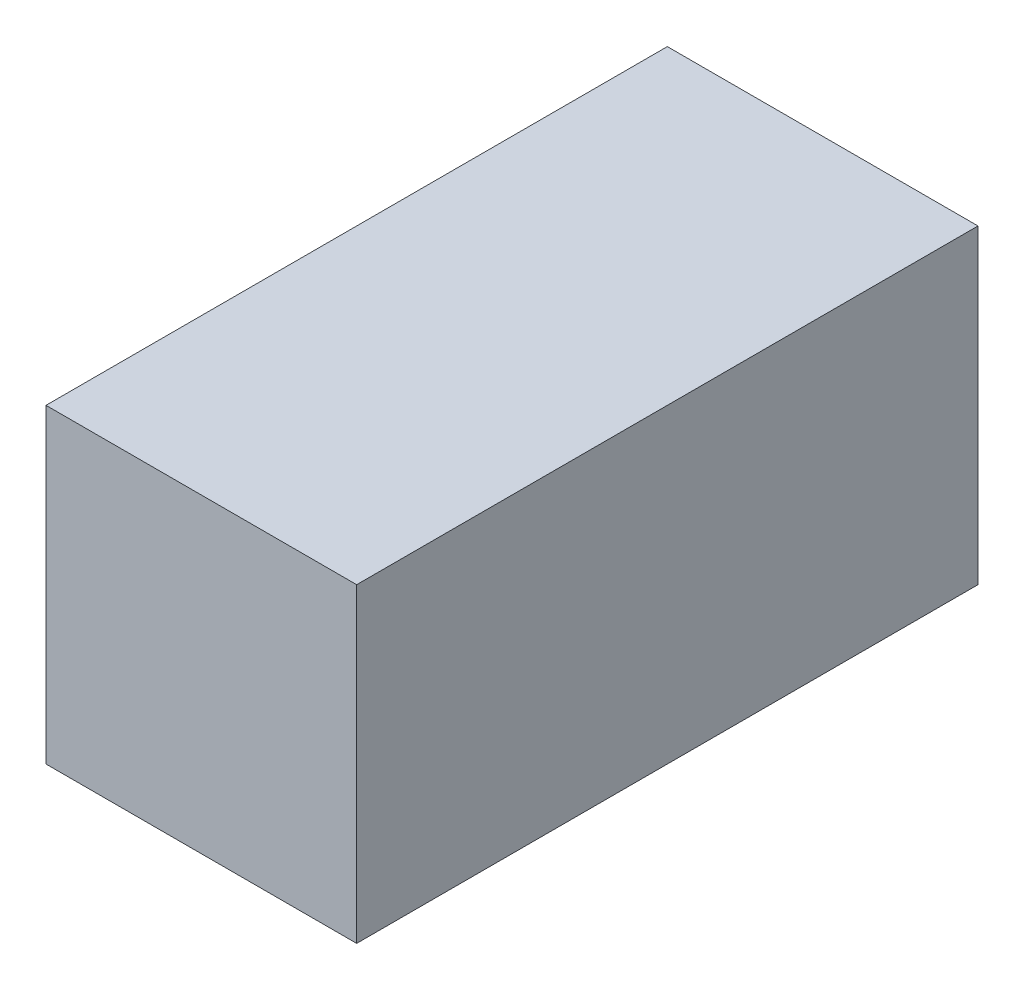
SolidWorks part; units mm, degrees
ref_plane "Front Plane" through (0, 0, 0) normal (0, 0, 1) x (1, 0, 0)
ref_plane "Top Plane" through (0, 0, 0) normal (0, 1, 0) x (1, 0, 0)
ref_plane "Right Plane" through (0, 0, 0) normal (1, 0, 0) x (0, 0, -1)
sketch "Sketch1" plane through (0, 0, 0) normal (0, 0, 1) x (1, 0, 0)
  line L1 (-9.4309, -12.2561) -> (10.5691, -12.2561)
  line L2 (-9.4309, -12.2561) -> (-9.4309, 7.7439)
  line L3 (-9.4309, 7.7439) -> (10.5691, 7.7439)
  line L4 (10.5691, -12.2561) -> (10.5691, 7.7439)
  line L5 (-9.4309, -12.2561) -> (10.5691, 7.7439) construction
  line L6 (-9.4309, 7.7439) -> (10.5691, -12.2561) construction
  dimension "D1" = 20
  dimension "D2" = 20
extrude "Boss-Extrude1" add sketch "Sketch1" along normal blind 40
sketch "Sketch2" plane through (0, 0, 0) normal (0, 0, -1) x (-1, 0, 0)
  line L0 (-0.5691, 7.7439) -> (-0.5691, -5.1168) construction
  line L1 (-10.5691, 7.7439) -> (9.4309, 7.7439) construction
  line L2 (-0.5691, -5.1168) -> (9.4309, -2.2561) construction
  line L3 (9.4309, 7.7439) -> (9.4309, -12.2561) construction
  line L4 (9.4309, -2.2561) -> (-0.5691, -2.2561) construction
  circle A0 centre (-0.5691, -2.2561) radius 5
extrude "Cut-Extrude1" cut sketch "Sketch2" against normal mid plane 20
